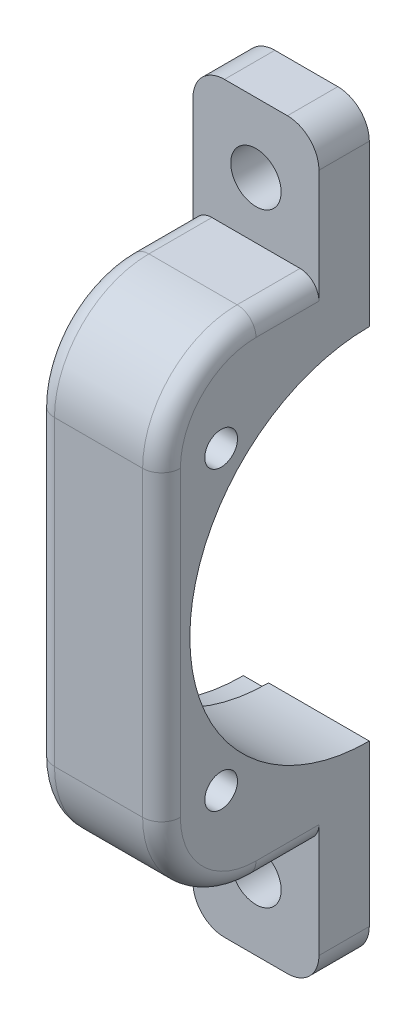
SolidWorks part; units mm, degrees
ref_plane "Plan de face" through (0, 0, 0) normal (0, 0, 1) x (1, 0, 0)
ref_plane "Plan de dessus" through (0, 0, 0) normal (0, 1, 0) x (1, 0, 0)
ref_plane "Plan de droite" through (0, 0, 0) normal (1, 0, 0) x (0, 0, -1)
sketch "Esquisse1" plane through (0, 0, 0) normal (0, 0, 1) x (1, 0, 0)
  line L1 (0, 0) -> (20, 0)
  line L2 (0, 0) -> (0, 78)
  line L3 (0, 78) -> (20, 78)
  line L4 (20, 0) -> (20, 78)
  dimension "D1" = 78
  dimension "D2" = 20
extrude "Boss.-Extru.1" add sketch "Esquisse1" along normal blind 33
sketch "Esquisse2" plane through (0, 78, 0) normal (0, 1, 0) x (1, 0, 0)
  line L0 (20, -33) -> (20, 0) construction
  line L1 (0, 0) -> (20, 0)
  line L2 (0, 0) -> (0, -8)
  line L3 (0, -8) -> (20, -8)
  line L4 (20, 0) -> (20, -8)
  dimension "D1" = 8
extrude "Boss.-Extru.2" add sketch "Esquisse2" along normal blind 20
sketch "Esquisse3" plane through (0, 0, 0) normal (0, -1, 0) x (1, 0, 0)
  line L0 (20, 33) -> (20, 0) construction
  line L1 (0, 0) -> (20, 0)
  line L2 (0, 0) -> (0, 8)
  line L3 (0, 8) -> (20, 8)
  line L4 (20, 0) -> (20, 8)
  dimension "D1" = 8
extrude "Boss.-Extru.3" add sketch "Esquisse3" along normal blind 20
sketch "Esquisse4" plane through (0, 0, 8) normal (0, 0, 1) x (1, 0, 0)
  line L3 (0, 39) -> (92.5, 39) construction
  line L4 (0, 78) -> (0, 0) construction
  line L7 (0, 98) -> (0, 78) construction
  line L8 (20, 78) -> (0, 78) construction
  circle A0 centre (10, 87) radius 4
  circle A3 centre (10, -9) radius 4
  dimension "D1" = 8
  dimension "D2" = 9
  dimension "D3" = 10
extrude "Enlèv. mat.-Extru.1" cut sketch "Esquisse4" against normal blind 10
fillet "Congé1" radius 5 4 edges at (20, 98, 4) (0, 98, 4) (0, -20, 4) (20, -20, 4)
sketch "Esquisse5" plane through (20, 0, 0) normal (1, 0, 0) x (0, 0, -1)
  line L0 (0, -15) -> (0, 93) construction
  circle A0 centre (0, 39) radius 28.5
  dimension "D1" = 57
extrude "Enlèv. mat.-Extru.2" cut sketch "Esquisse5" against normal blind 30
sketch "Esquisse6" plane through (20, 0, 0) normal (1, 0, 0) x (0, 0, -1)
  circle A0 centre (-23.529, 15.471) radius 2.6
  circle A1 centre (-23.529, 62.529) radius 2.6
extrude "Enlèv. mat.-Extru.3" cut sketch "Esquisse6" against normal blind 20
fillet "Congé4" radius 15 2 edges at (10, 0, 33) (10, 78, 33)
fillet "Congé5" radius 3 10 edges at (0, 0, 13) (0, 4.3934, 28.6066) (0, 39, 33) (0, 73.6066, 28.6066) (20, 0, 13) (20, 4.3934, 28.6066) (20, 39, 33) (20, 73.6066, 28.6066) (0, 78, 13) (20, 78, 13)
sketch "Esquisse7" plane through (0, 0, 0) normal (-1, 0, 0) x (0, 0, 1)
  line L0 (0, 67.5) -> (0, 10.5) construction
  circle A0 centre (0, 39) radius 29.5
  dimension "D1" = 59
extrude "Enlèv. mat.-Extru.4" cut sketch "Esquisse7" against normal blind 4
